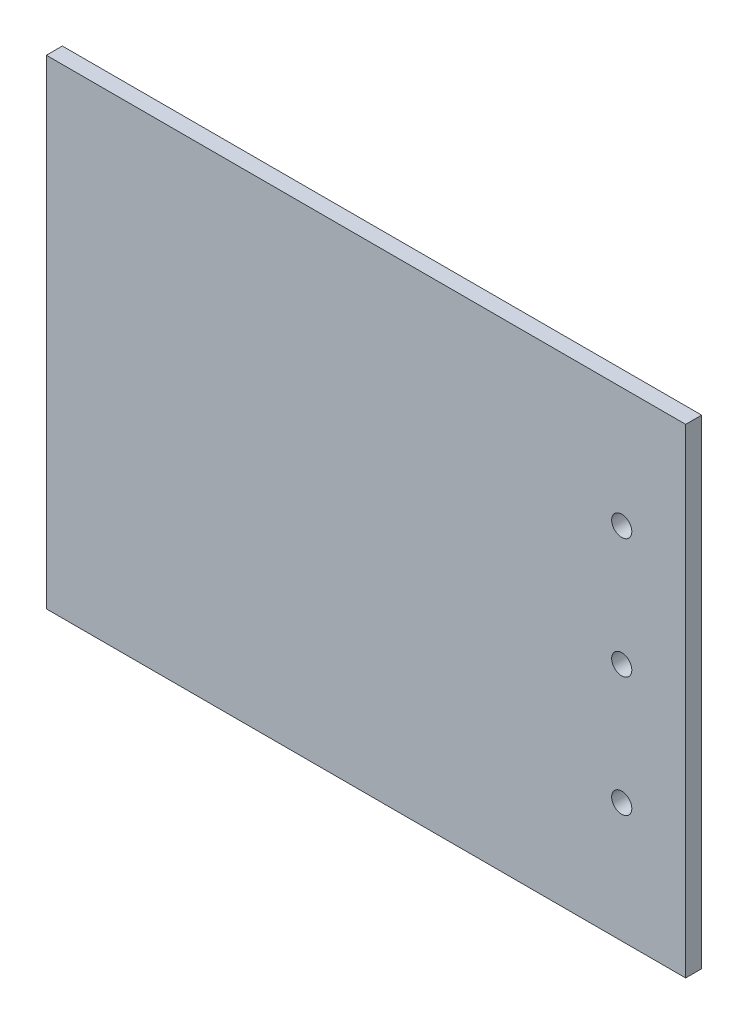
SolidWorks part; units mm, degrees
ref_plane "Front Plane" through (0, 0, 0) normal (0, 0, 1) x (1, 0, 0)
ref_plane "Top Plane" through (0, 0, 0) normal (0, 1, 0) x (1, 0, 0)
ref_plane "Right Plane" through (0, 0, 0) normal (1, 0, 0) x (0, 0, -1)
sketch "Sketch2" plane through (0, 0, 0) normal (0, 0, 1) x (1, 0, 0)
  line L0 (-223.5848, -75) -> (-198.805, -75)
  line L1 (-23.5848, 0) -> (-223.5848, 0)
  line L2 (-23.5848, 0) -> (-23.5848, -150)
  line L3 (-23.5848, -150) -> (-223.5848, -150)
  line L4 (-223.5848, 0) -> (-223.5848, -150)
  line L5 (-123.5848, 0) -> (-123.5848, -150) construction
  line L6 (-123.5848, -150) -> (-123.5848, -75) construction
  line L7 (-123.5848, -75) -> (-223.5848, -75) construction
  circle A0 centre (-43.5848, -37.5) radius 3.15
  circle A1 centre (-43.5848, -112.5) radius 3.15
  circle A2 centre (-43.5848, -75) radius 3.15
  dimension "D1" = 200
  dimension "D2" = 150
extrude "Boss-Extrude1" add sketch "Sketch2" along normal blind 5 contours L4 L3 L2 L1
sketch "Sketch3" plane through (0, 0, 0) normal (0, 0, -1) x (-1, 0, 0)
  circle A0 centre (43.5848, -37.5) radius 3.15
  circle A1 centre (43.5848, -75) radius 3.15
  circle A2 centre (43.5848, -112.5) radius 3.15
extrude "Cut-Extrude1" cut sketch "Sketch3" against normal blind 5
